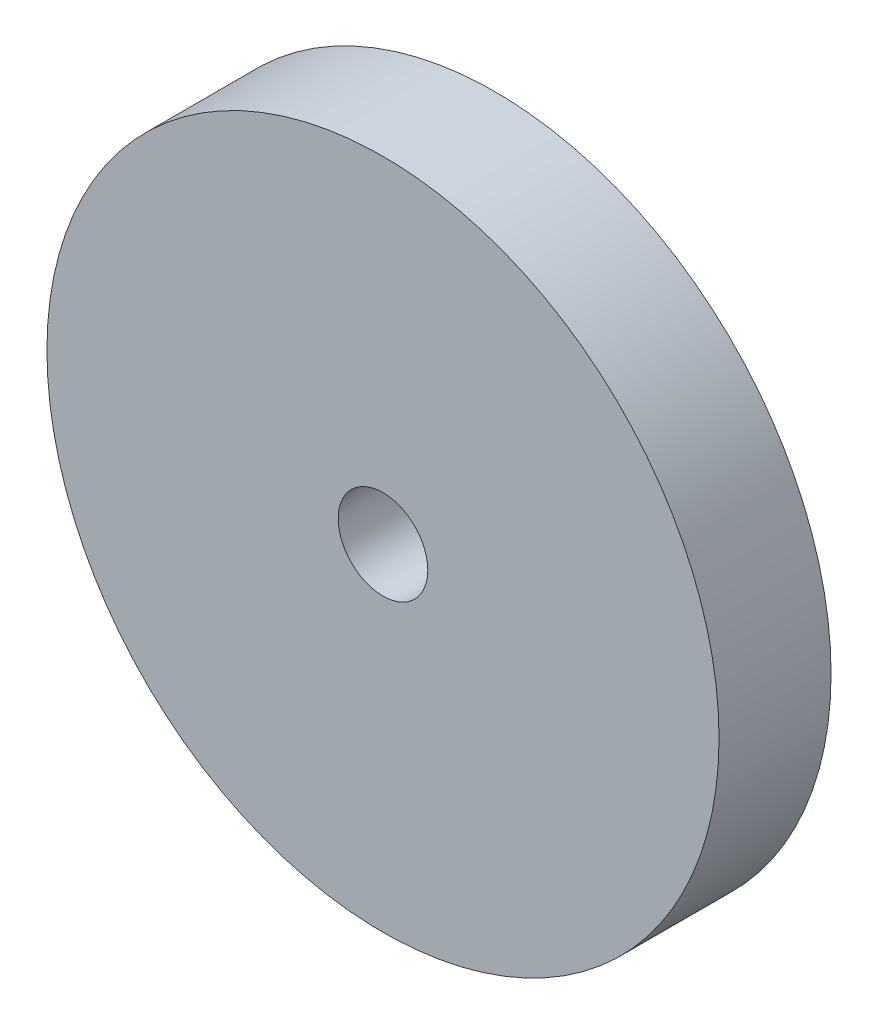
SolidWorks part; units mm, degrees
ref_plane "Alzado" through (0, 0, 0) normal (0, 0, 1) x (1, 0, 0)
ref_plane "Planta" through (0, 0, 0) normal (0, 1, 0) x (1, 0, 0)
ref_plane "Vista lateral" through (0, 0, 0) normal (1, 0, 0) x (0, 0, -1)
sketch "Croquis1" plane through (0, 0, 0) normal (0, 0, 1) x (1, 0, 0)
  circle A0 centre (0, 0) radius 15
extrude "Saliente-Extruir1" add sketch "Croquis1" along normal blind 5
sketch "Croquis2" plane through (0, 0, 5) normal (0, 0, 1) x (1, 0, 0)
  circle A1 centre (0, 0) radius 2
extrude "Cortar-Extruir1" cut sketch "Croquis2" against normal up to surface (5 mm away) up to face at (15, 0, 0)
